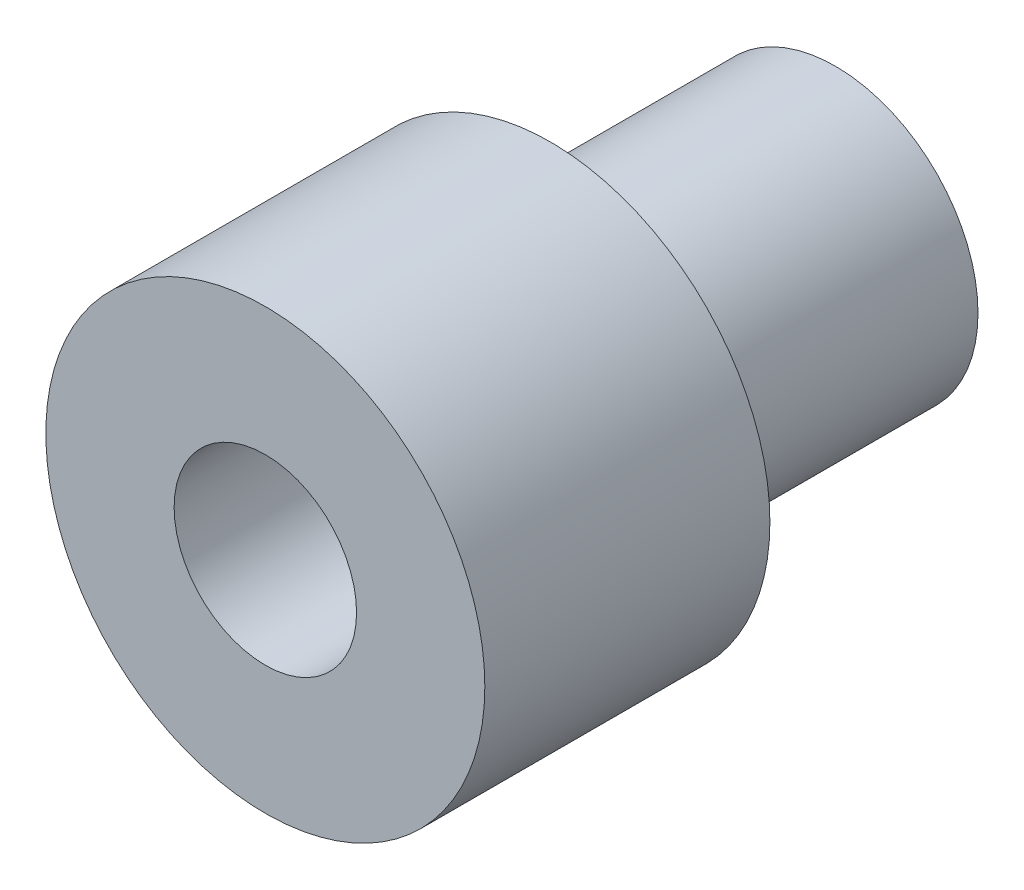
SolidWorks part; units mm, degrees
ref_plane "Front Plane" through (0, 0, 0) normal (0, 0, 1) x (1, 0, 0)
ref_plane "Top Plane" through (0, 0, 0) normal (0, 1, 0) x (1, 0, 0)
ref_plane "Right Plane" through (0, 0, 0) normal (1, 0, 0) x (0, 0, -1)
sketch "Sketch1" plane through (0, 0, 0) normal (1, 0, 0) x (0, 0, -1)
  line L0 (0, 1.6) -> (0, 3.85)
  line L1 (0, 3.85) -> (5, 3.85)
  line L2 (5, 3.85) -> (5, 2.5)
  line L3 (5, 2.5) -> (10, 2.5)
  line L4 (10, 2.5) -> (10, 1.6)
  line L5 (0, 1.6) -> (10, 1.6)
  line L6 (0, 0) -> (10, 0) construction
  dimension "D1" = 3.2
  dimension "D2" = 5
  dimension "D3" = 7.7
  dimension "D4" = 5
  dimension "D5" = 5
revolve "Revolve1" add sketch "Sketch1" angle 360 about L6
move or copy body "Body-Move/Copy1" [suppressed] bodies to move or copy 101
